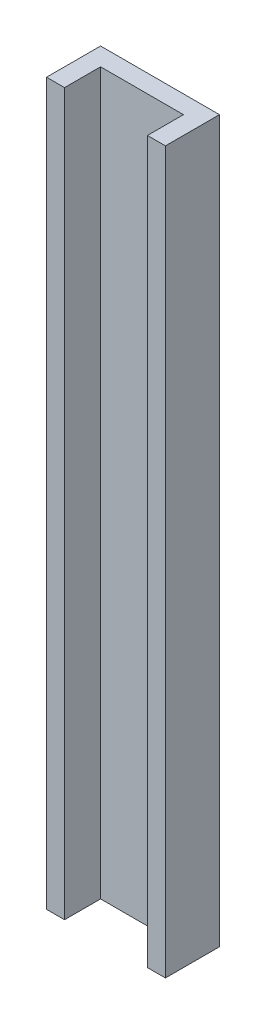
SolidWorks part; units mm, degrees
ref_plane "前视基准面" through (0, 0, 0) normal (0, 0, 1) x (1, 0, 0)
ref_plane "上视基准面" through (0, 0, 0) normal (0, 1, 0) x (1, 0, 0)
ref_plane "右视基准面" through (0, 0, 0) normal (1, 0, 0) x (0, 0, -1)
sketch "草图1" plane through (0, 0, 0) normal (0, 0, 1) x (1, 0, 0)
  line L1 (-16.5, -100) -> (16.5, -100)
  line L2 (-16.5, -100) -> (-16.5, 100)
  line L3 (-16.5, 100) -> (16.5, 100)
  line L4 (16.5, -100) -> (16.5, 100)
  line L5 (-16.5, -100) -> (16.5, 100) construction
  line L6 (-16.5, 100) -> (16.5, -100) construction
  point P0 (0, 0)
  dimension "D1" = 33
  dimension "D2" = 200
extrude "凸台-拉伸1" add sketch "草图1" along normal blind 5
sketch "草图2" plane through (0, 0, 5) normal (0, 0, 1) x (1, 0, 0)
  line L0 (-16.5, -100) -> (16.5, -100) construction
  line L1 (-16.5, 100) -> (-11.5, 100)
  line L2 (-16.5, 100) -> (-16.5, -100)
  line L3 (-16.5, -100) -> (-11.5, -100)
  line L4 (-11.5, 100) -> (-11.5, -100)
  line L6 (16.5, 100) -> (11.5, 100)
  line L7 (16.5, 100) -> (16.5, -100)
  line L8 (16.5, -100) -> (11.5, -100)
  line L9 (11.5, 100) -> (11.5, -100)
  dimension "D1" = 5
  dimension "D2" = 5
extrude "凸台-拉伸2" add sketch "草图2" along normal blind 10
